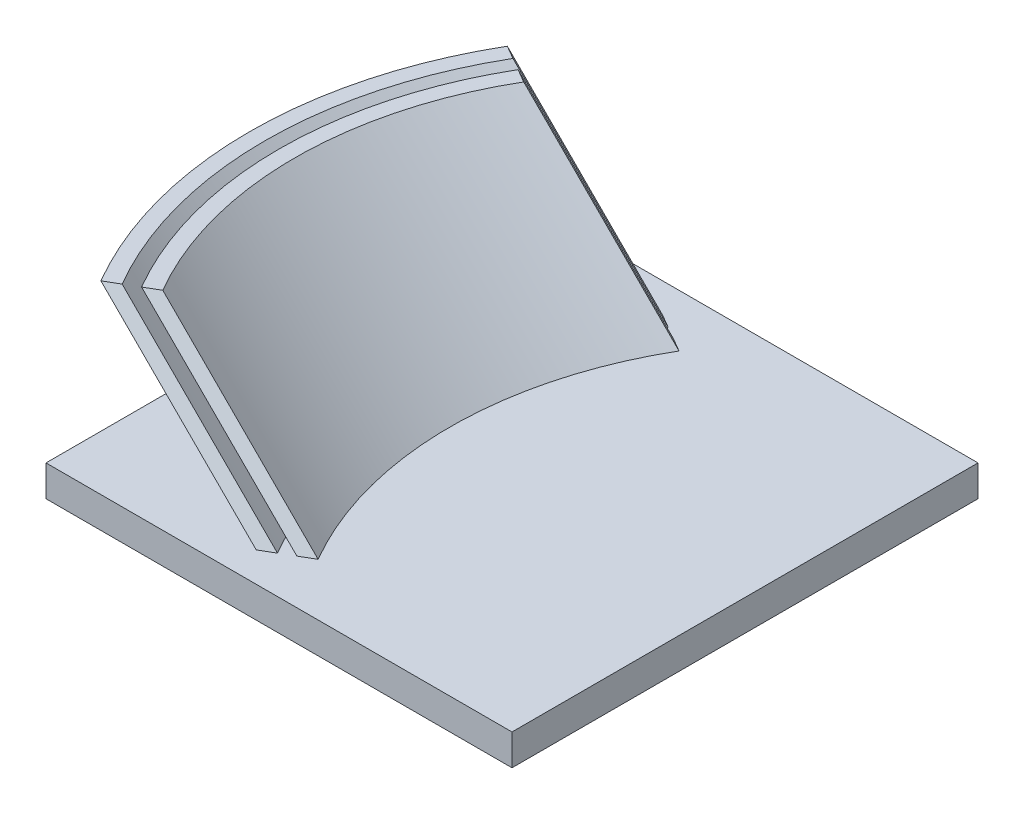
SolidWorks part; units mm, degrees
ref_plane "Front Plane" through (0, 0, 0) normal (0, 0, 1) x (1, 0, 0)
ref_plane "Top Plane" through (0, 0, 0) normal (0, 1, 0) x (1, 0, 0)
ref_plane "Right Plane" through (0, 0, 0) normal (1, 0, 0) x (0, 0, -1)
sketch "Sketch2" plane through (0, 0, 0) normal (0, 1, 0) x (1, 0, 0)
  line L0 (0, -15) -> (0, 15)
  line L21 (0, -47.4) -> (0, 0) construction
  line L22 (0, 0) -> (0, 47.4) construction
  line L24 (-15, 15) -> (15, 15)
  line L25 (-15, 15) -> (-15, -15)
  line L26 (-15, -15) -> (15, -15)
  line L27 (15, 15) -> (15, -15)
  point P2 (0, 0)
  point P22 (0, 0)
  dimension "D4" = 30
extrude "Boss-Extrude1" add sketch "Sketch2" along normal blind 2 contours L24 L27 L26 L25
sketch "Sketch3" plane through (0, 2, 0) normal (0, 1, 0) x (1, 0, 0)
  line L0 (-5, 15) -> (-5, -15) construction
  line L1 (-15, 15) -> (15, 15) construction
  line L2 (-15, -15) -> (15, -15) construction
  line L3 (-15, 15) -> (-15, -15) construction
  point P8 (-5, 0)
  dimension "D1" = 10
sketch "Sketch12" plane through (0, 2, 0) normal (0, 1, 0) x (1, 0, 0)
  line L0 (19.0856, 0) -> (-6.6753, 15) construction
  line L1 (19.0856, 0) -> (-6.6753, -15) construction
  line L2 (-1.7286, 12.1196) -> (-5, 0) construction
  line L3 (-5, 0) -> (-1.7286, -12.1196) construction
  line L4 (-15, 15) -> (15, 15) construction
  line L5 (-15, -15) -> (15, -15) construction
  line L6 (-5, 15) -> (-5, -15) construction
  line L9 (-15, 15) -> (-15, -15) construction
  line L10 (15, 15) -> (15, -15) construction
  line L11 (-15, 0) -> (-5.9144, 0) construction
  line L12 (-0.8644, 11.6164) -> (-1.7286, 12.1196)
  line L13 (-2.5188, 12.5797) -> (-3.383, 13.0829)
  line L14 (-0.8644, -11.6164) -> (-1.7286, -12.1196)
  line L15 (-2.5188, -12.5797) -> (-3.383, -13.0829)
  line L16 (-5, 0) -> (15, 0) construction
  arc A0 (-0.8644, 11.6164) -> (-0.8644, -11.6164) centre (19.0856, 0) ccw
  arc A1 (-3.383, 13.0829) -> (-3.383, -13.0829) centre (19.0856, 0) ccw
  arc A2 (-2.5188, -12.5797) -> (-2.5188, 12.5797) centre (19.0856, 0) cw
  arc A3 (-1.7286, -12.1196) -> (-1.7286, 12.1196) centre (19.0856, 0) cw
  point P11 (-5, 0)
  point P12 (0, 0)
  point P29 (-15, 0)
  point P30 (15, 0)
  dimension "D1" = 25
  dimension "D3" = 1
  dimension "D4" = 1
  dimension "D5" = 0.9144
  dimension "D7" = 0.9144
  dimension "D2" = 25.4
ref_plane "Plane1" through (0, 0, 0) normal (0, 0, 1) x (1, 0, 0)
sketch "Sketch13" plane through (0, 0, 0) normal (0, 0, 1) x (1, 0, 0)
  line L0 (15, 2) -> (5, 12)
  line L1 (-15, 2) -> (-5.9144, 2) construction
  line L2 (-15, 2) -> (15, 2) construction
  point P0 (13.2557, 2)
  point P5 (0, 0)
  point P6 (-0.6812, 2)
  point P8 (0, 0)
  dimension "D1" = 45
  dimension "D2" = 10
sweep "Sweep1" add profiles "Sketch12" path "Sketch13"
sketch "Sketch14" plane through (4.2602, 4.2602, 7.3164) normal (0.4495, 0.4495, 0.772) x (0.8933, -0.2262, -0.3884)
  line L0 (-9.4552, -2.2465) -> (-9.8975, -2.8195)
  line L1 (-6.7042, -4.3701) -> (-17.8989, 4.2716) construction
  line L2 (-7.5888, -4.6016) -> (-18.7835, 4.0401) construction
  line L3 (-9.8975, -2.8195) -> (-7.5888, -4.6016)
  line L4 (-7.5888, -4.6016) -> (-6.7042, -4.3701)
  line L5 (-6.7042, -4.3701) -> (-9.4552, -2.2465)
  line L6 (-19.6782, -5.8195) -> (7.1203, -5.8195) construction
  dimension "D1" = 90
  dimension "D2" = 3
sketch "Sketch17" plane through (0, 2, 0) normal (0, -1, 0) x (1, 0, 0)
  line L0 (16.5, 0) -> (-16.5, 0) construction
  circle A0 centre (-4.9425, 5) radius 0.4572
  circle A1 centre (-5.4572, 0) radius 0.4572
  circle A2 centre (-4.9425, -5) radius 0.4572
  arc A3 (-2.5188, 12.5797) -> (-2.5188, -12.5797) centre (19.0856, 0) ccw construction
  arc A4 (-1.7286, 12.1196) -> (-1.7286, -12.1196) centre (19.0856, 0) ccw construction
  point P12 (0, 0)
  point P15 (0, 0)
  dimension "D1" = 5
  dimension "D2" = 5
equation "\"mountWallThickness\"= 1.00mm"
equation "\"arcLength\"= 25.4000mm"
equation "\"tapeSpringThickness\"= 0.9144mm"
equation "\"curvatureRadius\"= 25.000mm"
equation "\"distanceBetweenWires\"= 7mm"
equation "\"D1@Sketch12\"=\"curvatureRadius\""
equation "\"D2@Sketch12\"=\"arcLength\""
equation "\"D3@Sketch12\"=\"mountWallThickness\""
equation "\"D4@Sketch12\"=\"mountWallThickness\""
equation "\"D5@Sketch12\"=\"tapeSpringThickness\""
equation "\"D7@Sketch12\"=\"tapeSpringThickness\""
